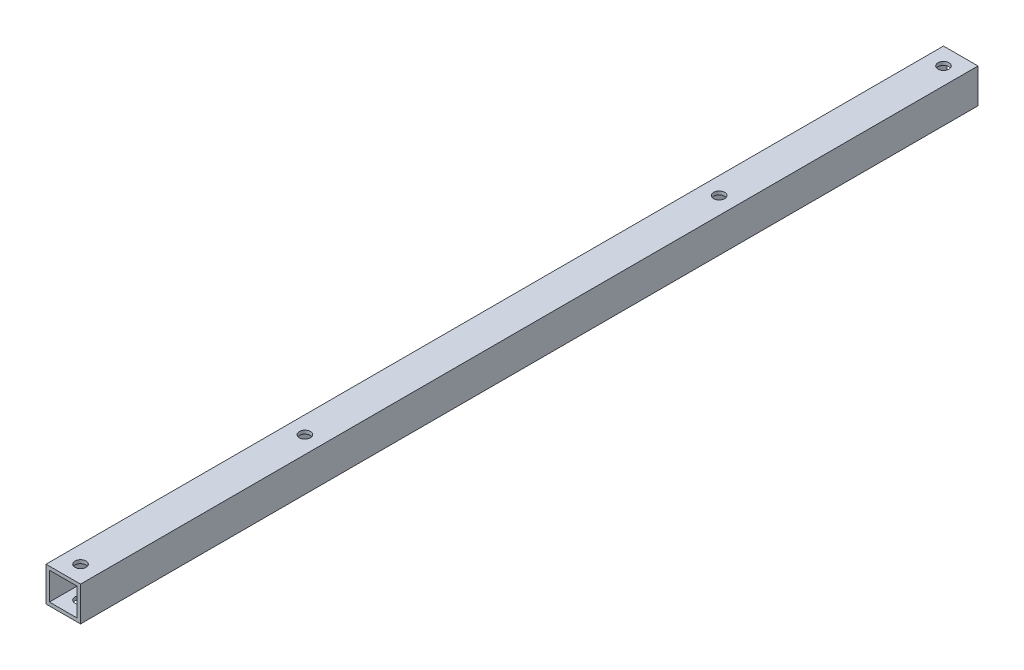
SolidWorks part; units mm, degrees
material "6061 合金"
ref_plane "正面" through (0, 0, 0) normal (0, 0, 1) x (1, 0, 0)
ref_plane "平面" through (0, 0, 0) normal (0, 1, 0) x (1, 0, 0)
ref_plane "右側面" through (0, 0, 0) normal (1, 0, 0) x (0, 0, -1)
sketch "断面 スケッチ" plane through (0, 0, 0) normal (0, 0, 1) x (1, 0, 0)
  line L1 (-5, -5) -> (5, -5)
  line L2 (-5, -5) -> (-5, 5)
  line L3 (-5, 5) -> (5, 5)
  line L4 (5, -5) -> (5, 5)
  line L5 (-5, -5) -> (5, 5) construction
  line L6 (-5, 5) -> (5, -5) construction
  point P0 (0, 0)
  dimension "D1" = 10
extrude "フレーム全長" add sketch "断面 スケッチ" along normal blind 260 thin thin type one direction reverse wall 1
sketch "上面穴 スケッチ" plane through (0, 5, 0) normal (0, 1, 0) x (1, 0, 0)
  line L0 (0, 0) -> (0, -260) construction
  line L1 (5, 0) -> (-5, 0) construction
  line L2 (5, -260) -> (-5, -260) construction
  line L3 (-5, -130) -> (5, -130) construction
  line L4 (-5, -260) -> (-5, 0) construction
  line L5 (5, -260) -> (5, 0) construction
  circle A0 centre (0, -5) radius 1.6
  circle A1 centre (0, -70) radius 1.6
  circle A2 centre (0, -190) radius 1.6
  circle A3 centre (0, -255) radius 1.6
  dimension "D1" = 5
  dimension "D2" = 3.2
  dimension "D3" = 65
sketch "側面穴 スケッチ" plane through (5, 0, 0) normal (1, 0, 0) x (0, 0, -1)
  line L0 (0, 0) -> (-260, 0) construction
  line L1 (0, -5) -> (0, 5) construction
  line L2 (-260, -5) -> (-260, 5) construction
  line L3 (-130, 5) -> (-130, -5) construction
  line L4 (-260, 5) -> (0, 5) construction
  line L5 (-260, -5) -> (0, -5) construction
  circle A0 centre (-15, 0) radius 1.6
  dimension "D1" = 15
  dimension "D2" = 3.2
extrude "上面穴貫通" cut sketch "上面穴 スケッチ" against normal through all
extrude "側面穴貫通" [suppressed] cut sketch "側面穴 スケッチ" against normal through all
fillet "フィレット" [suppressed] radius 5
